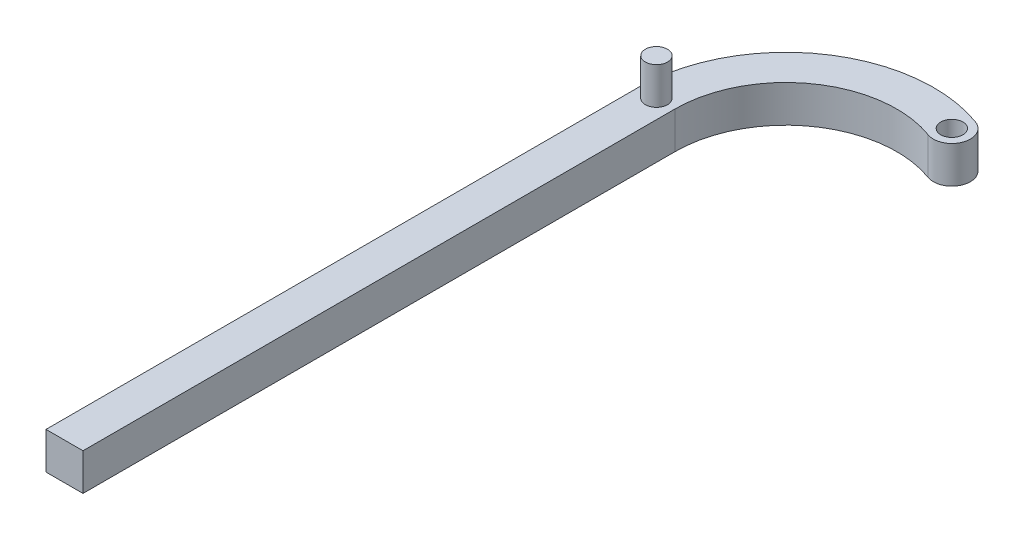
SolidWorks part; units mm, degrees
ref_plane "Front Plane" through (0, 0, 0) normal (0, 0, 1) x (1, 0, 0)
ref_plane "Top Plane" through (0, 0, 0) normal (0, 1, 0) x (1, 0, 0)
ref_plane "Right Plane" through (0, 0, 0) normal (1, 0, 0) x (0, 0, -1)
sketch "Sketch1" plane through (0, 0, 0) normal (0, 1, 0) x (1, 0, 0)
  circle A0 centre (0, 0) radius 20
  dimension "D1" = 40
extrude "Boss-Extrude1" add sketch "Sketch1" along normal blind 5
sketch "Sketch2" plane through (0, 5, 0) normal (0, 1, 0) x (1, 0, 0)
  circle A0 centre (0, 0) radius 15
  dimension "D1" = 30
extrude "Cut-Extrude1" cut sketch "Sketch2" against normal blind 5
sketch "Sketch3" plane through (0, 5, 0) normal (0, 1, 0) x (1, 0, 0)
  line L0 (6.8404, 18.7939) -> (0, 0)
  line L1 (0, 0) -> (-20, 0)
  line L2 (0.8679, 2.3845) -> (6.8404, 18.7939)
  arc A0 (-20, 0) -> (6.8404, 18.7939) centre (0, 0) ccw
  circle A1 centre (0, 0) radius 20 construction
  circle M1 centre (0, 0) radius 15
  circle M2 centre (0, 0) radius 20
extrude "Cut-Extrude3" cut sketch "Sketch3" against normal blind 5 contours L1 L0 M1 M2
sketch "Sketch7" plane through (0, 5, 0) normal (0, 1, 0) x (1, 0, 0)
  line L0 (-15, 0) -> (-15, -80)
  line L1 (-15, -80) -> (-20, -80)
  line L2 (-20, -80) -> (-20, 0)
  line L5 (5.1303, 14.0954) -> (6.8404, 18.7939)
  line L6 (-20, 0) -> (-15, 0)
  line L8 (-20, 0) -> (-15, 0)
  arc A2 (6.8404, 18.7939) -> (-20, 0) centre (0, 0) ccw
  arc A3 (5.1303, 14.0954) -> (-15, 0) centre (0, 0) ccw
  dimension "D1" = 5
  dimension "D2" = 80
  dimension "D3" = 0
extrude "Boss-Extrude2" add sketch "Sketch7" against normal blind 5 contours L2 L8 L0 L1
sketch "Sketch9" plane through (0, 5, 0) normal (0, 1, 0) x (1, 0, 0)
  line L0 (6.8404, 18.7939) -> (5.1303, 14.0954) construction
  line L1 (6.8404, 18.7939) -> (5.1303, 14.0954)
  arc A0 (5.1303, 14.0954) -> (6.8404, 18.7939) centre (5.9854, 16.4446) ccw
extrude "Boss-Extrude3" add sketch "Sketch9" against normal blind 5
sketch "Sketch10" plane through (0, 5, 0) normal (0, 1, 0) x (1, 0, 0)
  circle A0 centre (5.9854, 16.4446) radius 1.5
  dimension "D1" = 3
extrude "Cut-Extrude4" cut sketch "Sketch10" against normal blind 5
sketch "Sketch11" plane through (0, 5, 0) normal (0, 1, 0) x (1, 0, 0)
  circle A0 centre (-17.5, 0) radius 1.5
  dimension "D1" = 3
  dimension "D2" = 17.5
extrude "Boss-Extrude4" add sketch "Sketch11" along normal blind 5 contours A0
